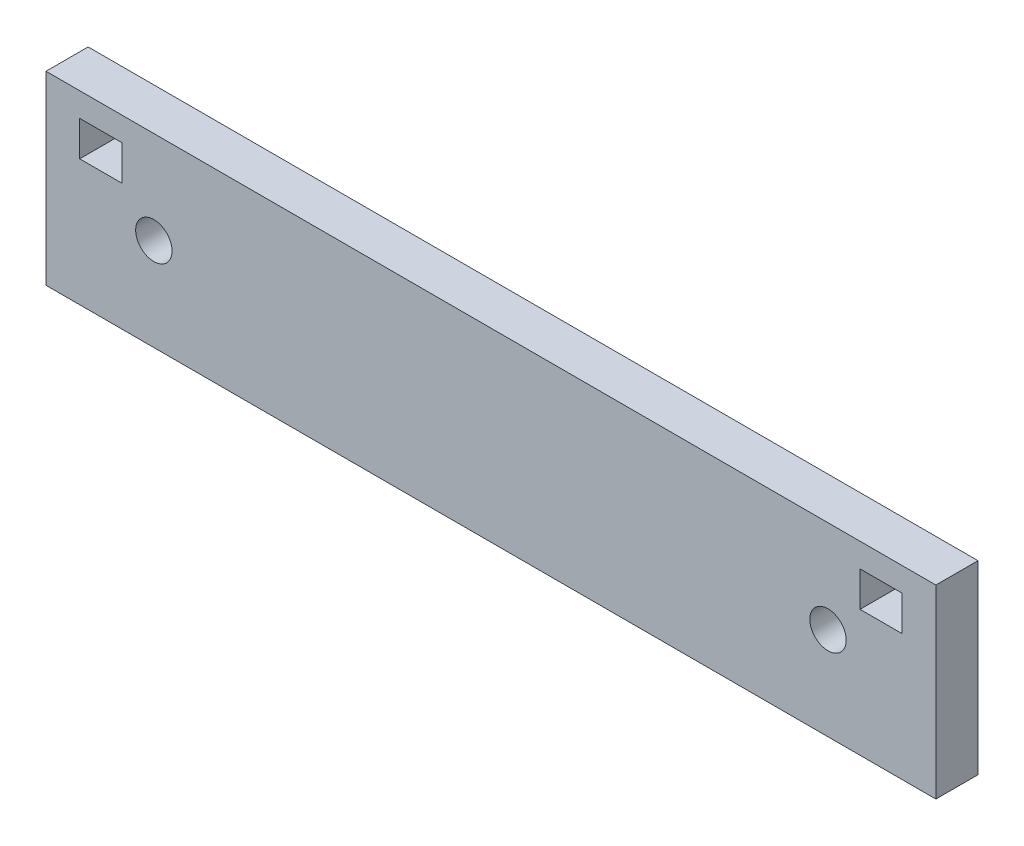
SolidWorks part; units mm, degrees
material "Beech"
ref_plane "Front Plane" through (0, 0, 0) normal (0, 0, 1) x (1, 0, 0)
ref_plane "Top Plane" through (0, 0, 0) normal (0, 1, 0) x (1, 0, 0)
ref_plane "Right Plane" through (0, 0, 0) normal (1, 0, 0) x (0, 0, -1)
sketch "Sketch1" plane through (0, 0, 0) normal (0, 0, 1) x (1, 0, 0)
  line L0 (15.494, 1.27) -> (13.9065, 1.27)
  line L1 (16.764, -3.4925) -> (-16.764, -3.4925)
  line L2 (16.764, -3.4925) -> (16.764, 3.4925)
  line L3 (16.764, 3.4925) -> (-16.764, 3.4925)
  line L4 (-16.764, -3.4925) -> (-16.764, 3.4925)
  line L5 (16.764, -3.4925) -> (-16.764, 3.4925) construction
  line L6 (16.764, 3.4925) -> (-16.764, -3.4925) construction
  line L7 (13.9065, 1.27) -> (13.9065, 2.5908)
  line L8 (13.9065, 2.5908) -> (15.494, 2.5908)
  line L9 (15.494, 2.5908) -> (15.494, 1.27)
  line L12 (0, -1000) -> (0, 49000) construction
  line L13 (-1000, 0) -> (49000, 0) construction
  line L37 (-15.494, 2.5908) -> (-15.494, 1.27)
  line L38 (-15.494, 1.27) -> (-13.9065, 1.27)
  line L39 (-13.9065, 1.27) -> (-13.9065, 2.5908)
  line L40 (-13.9065, 2.5908) -> (-15.494, 2.5908)
  circle A0 centre (-12.7, 0) radius 0.6858
  circle A1 centre (12.7, 0) radius 0.6858
  point P0 (0, 0)
  dimension "D6" = 12.7
  dimension "D7" = 1.3208
  dimension "D5" = 1.3716
  dimension "D1" = 6.985
  dimension "D2" = 33.528
  dimension "D3" = 1.27
  dimension "D4" = 0.9017
  dimension "D8" = 1.5875
extrude "Boss-Extrude1" add sketch "Sketch1" along normal blind 1.5875
